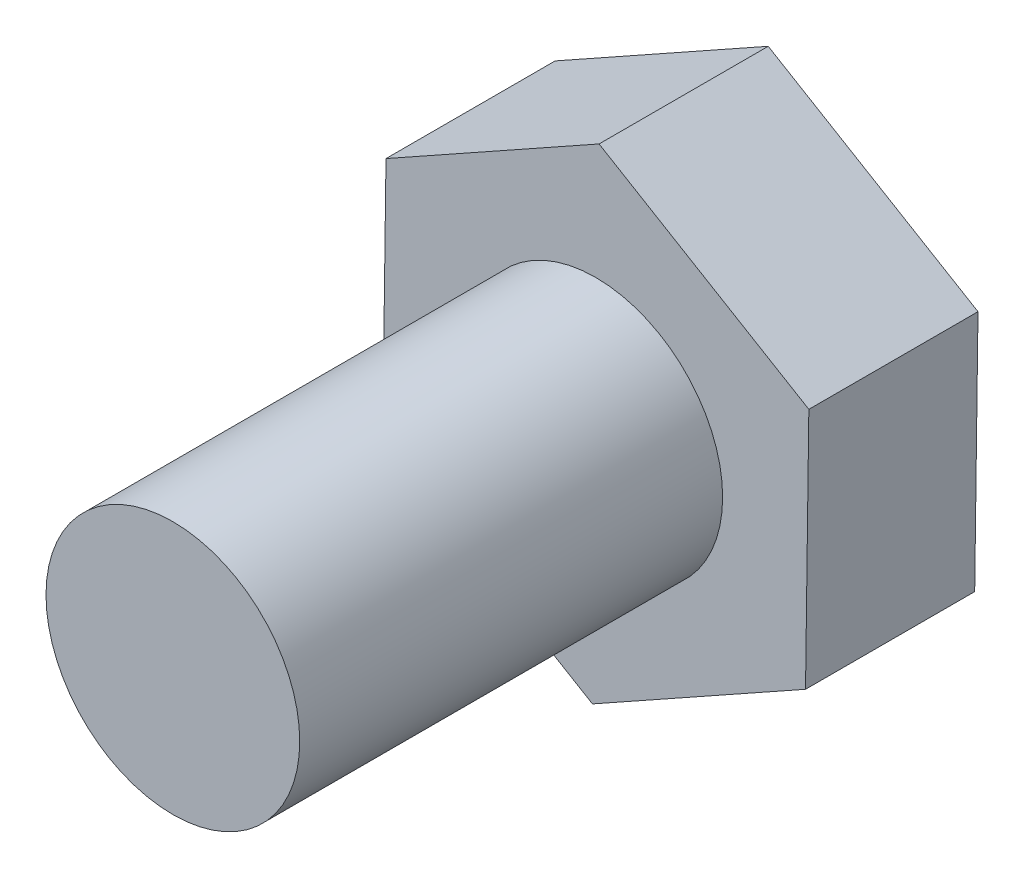
SolidWorks part; units mm, degrees
material "Нержавеющая сталь (ферритная)"
ref_plane "Front" through (0, 0, 0) normal (0, 0, 1) x (1, 0, 0)
ref_plane "Top" through (0, 0, 0) normal (0, 1, 0) x (1, 0, 0)
ref_plane "Right" through (0, 0, 0) normal (1, 0, 0) x (0, 0, -1)
sketch "Эскиз1" plane through (0, 0, 0) normal (0, 0, 1) x (1, 0, 0)
  line L1 (4.9604, -2.9543) -> (5.0387, 2.8186)
  line L2 (5.0387, 2.8186) -> (0.0783, 5.773)
  line L3 (0.0783, 5.773) -> (-4.9604, 2.9543)
  line L4 (-4.9604, 2.9543) -> (-5.0387, -2.8186)
  line L5 (-5.0387, -2.8186) -> (-0.0783, -5.773)
  line L6 (-0.0783, -5.773) -> (4.9604, -2.9543)
  circle A0 centre (0, 0) radius 5 construction
  dimension "D1" = 10
extrude "Бобышка-Вытянуть1" add sketch "Эскиз1" along normal blind 4
sketch "Эскиз2" plane through (0, 0, 4) normal (0, 0, 1) x (1, 0, 0)
  circle A0 centre (0, 0) radius 3
extrude "Бобышка-Вытянуть2" add sketch "Эскиз2" along normal blind 10
